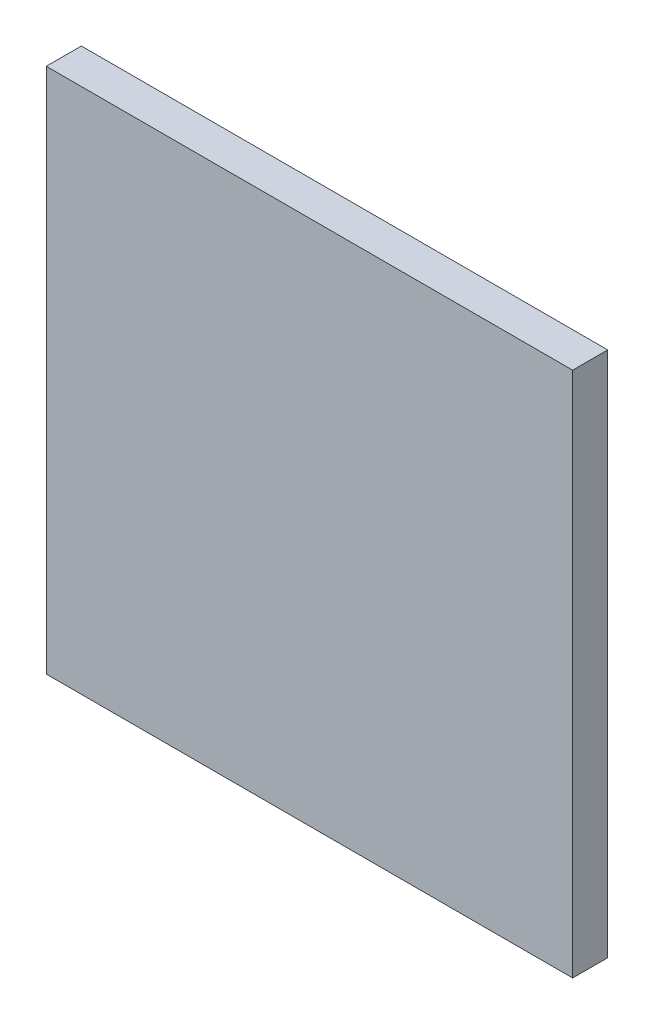
SolidWorks part; units mm, degrees
ref_plane "Front Plane" through (0, 0, 0) normal (0, 0, 1) x (1, 0, 0)
ref_plane "Top Plane" through (0, 0, 0) normal (0, 1, 0) x (1, 0, 0)
ref_plane "Right Plane" through (0, 0, 0) normal (1, 0, 0) x (0, 0, -1)
sketch "Sketch1" plane through (0, 0, 0) normal (0, 0, 1) x (1, 0, 0)
  line L1 (0, 0) -> (285.75, 0)
  line L2 (0, 0) -> (0, 285.75)
  line L3 (0, 285.75) -> (285.75, 285.75)
  line L4 (285.75, 0) -> (285.75, 285.75)
  dimension "D1" = 285.75
extrude "Boss-Extrude1" add sketch "Sketch1" along normal blind 19.05
